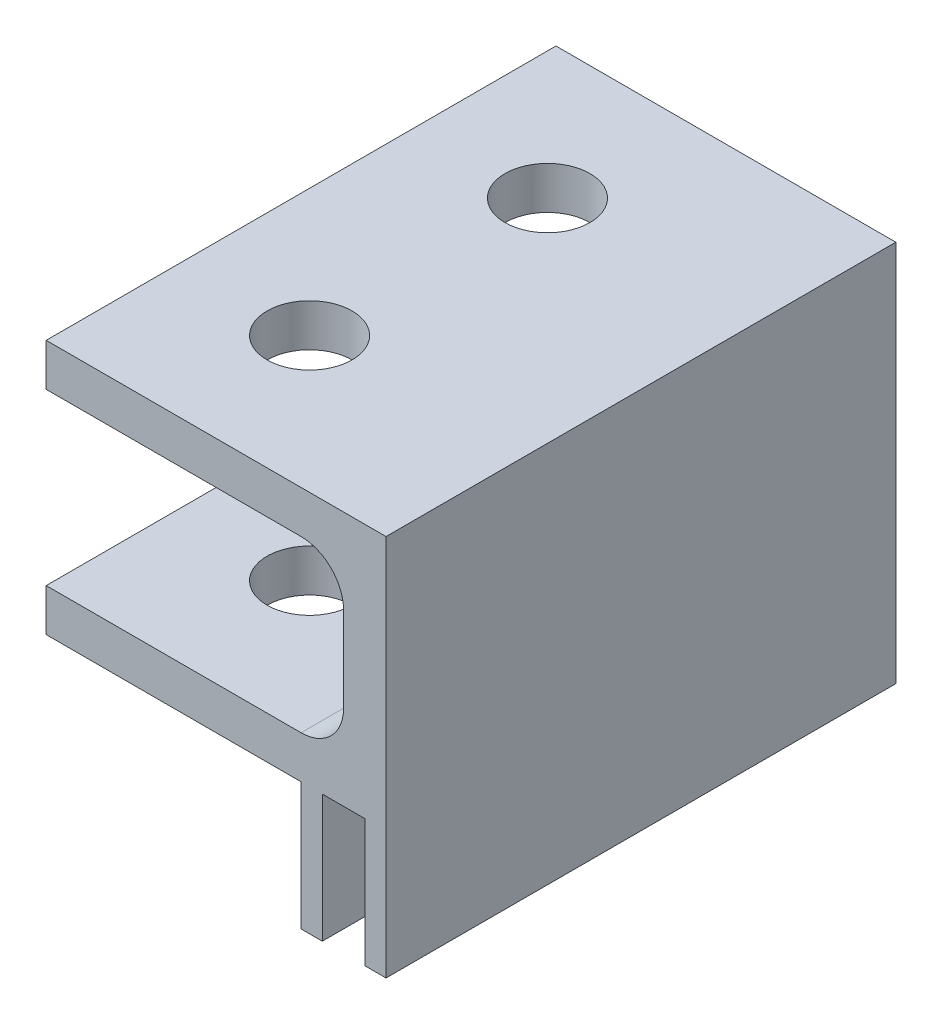
SolidWorks part; units mm, degrees
ref_plane "Front Plane" through (0, 0, 0) normal (0, 0, 1) x (1, 0, 0)
ref_plane "Top Plane" through (0, 0, 0) normal (0, 1, 0) x (1, 0, 0)
ref_plane "Right Plane" through (0, 0, 0) normal (1, 0, 0) x (0, 0, -1)
sketch "Sketch1" plane through (0, 0, 0) normal (0, 0, 1) x (1, 0, 0)
  line L0 (0, 0) -> (35, 0)
  line L1 (35, 0) -> (35, -20)
  line L2 (35, -20) -> (0, -20)
  line L3 (0, -20) -> (0, -25)
  line L4 (0, -25) -> (40, -25)
  line L5 (40, -25) -> (40, 5)
  line L6 (40, 5) -> (0, 5)
  line L7 (0, 5) -> (0, 0)
  dimension "D1" = 5
  dimension "D2" = 5
  dimension "D3" = 5
  dimension "D4" = 35
  dimension "D5" = 20
extrude "Boss-Extrude1" add sketch "Sketch1" along normal blind 60
fillet "Fillet1" radius 5 2 edges at (35, -20, 30) (35, 0, 30)
sketch "Sketch2" plane through (0, 5, 0) normal (0, 1, 0) x (1, 0, 0)
  line L0 (0, -30) -> (40, -30) construction
  line L1 (0, -60) -> (0, 0) construction
  line L2 (40, -60) -> (40, 0) construction
  circle A0 centre (15, -44) radius 5
  circle A2 centre (15, -16) radius 5
  dimension "D1" = 14
  dimension "D2" = 10
  dimension "D3" = 15
extrude "Cut-Extrude1" cut sketch "Sketch2" against normal blind 75 contours A0 | A2
sketch "Sketch3" plane through (0, -25, 0) normal (0, -1, 0) x (1, 0, 0)
  line L0 (0, 0) -> (40, 0) construction
  line L2 (32.5, 0) -> (32.5, 60)
  line L4 (37.5, 0) -> (37.5, 60)
  line L5 (0, 60) -> (40, 60) construction
  line L6 (40, 60) -> (40, 0) construction
  line L8 (37.5, 0) -> (40, 0)
  line L9 (37.5, 0) -> (37.5, 60)
  line L10 (37.5, 60) -> (40, 60)
  line L11 (40, 0) -> (40, 60)
  line L12 (32.5, 0) -> (30, 0)
  line L13 (32.5, 0) -> (32.5, 60)
  line L14 (32.5, 60) -> (30, 60)
  line L15 (30, 0) -> (30, 60)
  line M10 (0, 0) -> (40, 0)
  line M11 (40, 0) -> (40, 60)
  line M12 (40, 60) -> (0, 60)
  dimension "D1" = 5
  dimension "D2" = 2.5
  dimension "D3" = 2.5
extrude "Boss-Extrude2" add sketch "Sketch3" along normal blind 15 contours L15 L2 M10 M12 | L4 M10 M11 M12
